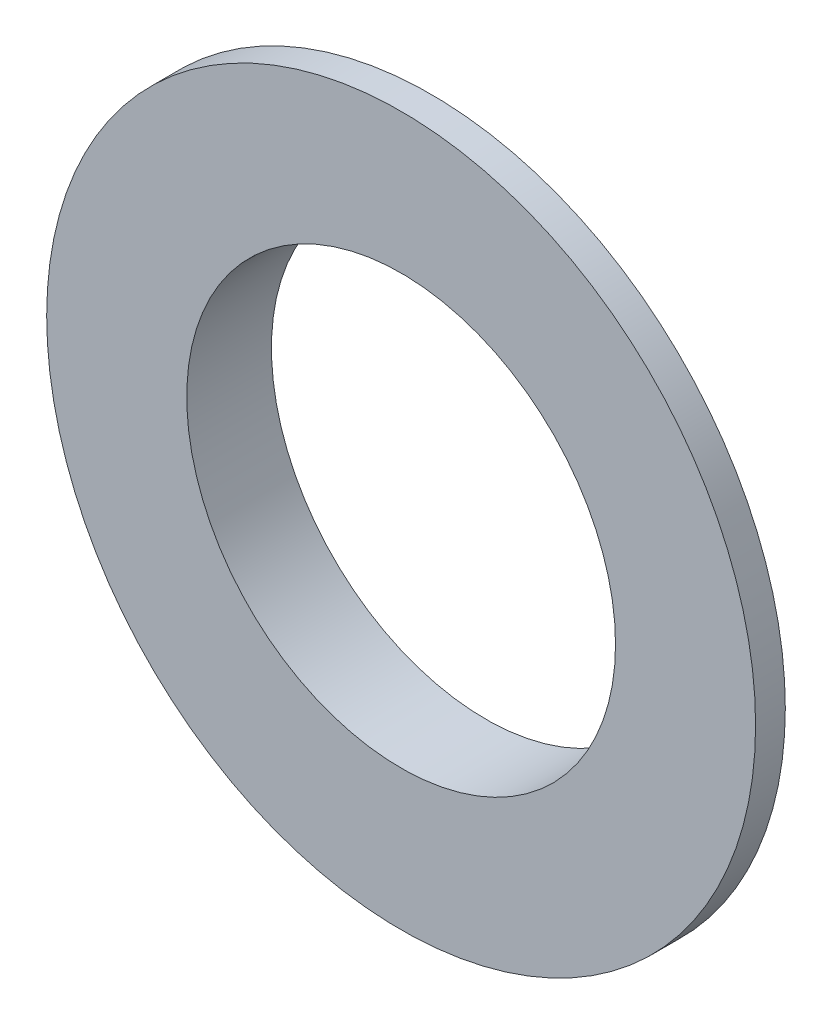
SolidWorks part; units mm, degrees
ref_plane "Front Plane" through (0, 0, 0) normal (0, 0, 1) x (1, 0, 0)
ref_plane "Top Plane" through (0, 0, 0) normal (0, 1, 0) x (1, 0, 0)
ref_plane "Right Plane" through (0, 0, 0) normal (1, 0, 0) x (0, 0, -1)
sketch "Sketch1" plane through (0, 0, 0) normal (0, 0, 1) x (1, 0, 0)
  circle A0 centre (0, 0) radius 5.95
  circle A1 centre (0, 0) radius 7.5375
  dimension "D1" = 11.9
  dimension "D2" = 1.5875
extrude "Boss-Extrude1" add sketch "Sketch1" along normal blind 1.525
sketch "Sketch2" plane through (0, 0, 1.525) normal (0, 0, 1) x (1, 0, 0)
  circle A0 centre (0, 0) radius 5.95
  circle A1 centre (0, 0) radius 9.8375
  circle A2 centre (0, 0) radius 7.5375 construction
  dimension "D1" = 2.3
  dimension "D2" = 11.9
extrude "Boss-Extrude2" add sketch "Sketch2" along normal blind 0.825
